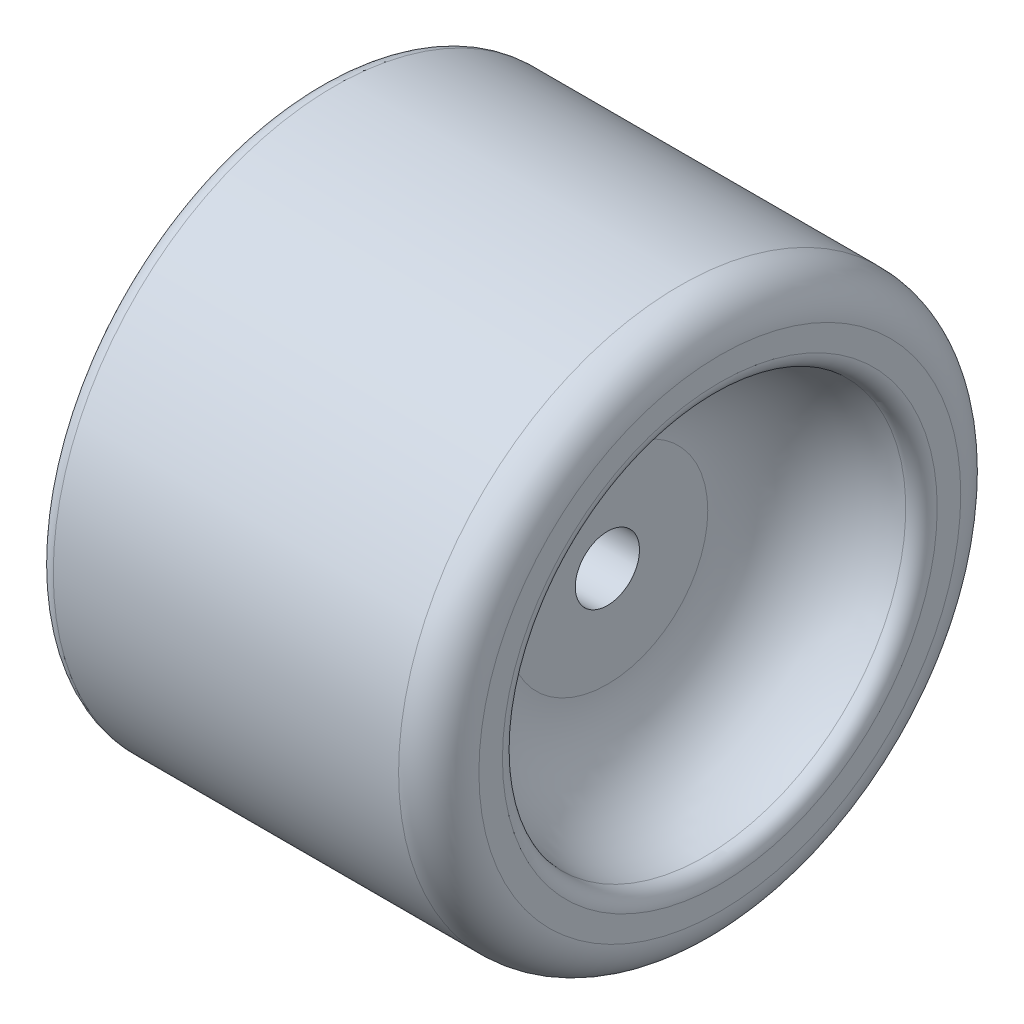
SolidWorks part; units mm, degrees
ref_plane "Front Plane" through (0, 0, 0) normal (0, 0, 1) x (1, 0, 0)
ref_plane "Top Plane" through (0, 0, 0) normal (0, 1, 0) x (1, 0, 0)
ref_plane "Right Plane" through (0, 0, 0) normal (1, 0, 0) x (0, 0, -1)
ref_plane "Plane1" through (0, 0, 0) normal (0, 0, -1) x (-1, 0, 0)
sketch "Sketch1" plane through (0, 0, 0) normal (0, 0, -1) x (-1, 0, 0)
  line L0 (0, 4) -> (22, 4)
  line L1 (22, 4) -> (22, 12.5)
  line L2 (22, 12.5) -> (24.5624, 12.5)
  line L3 (36, 29.2029) -> (36, 33)
  line L4 (34, 35) -> (-9, 35)
  line L5 (-14, 30) -> (-14, 27.0688)
  line L6 (0, 12.5) -> (0, 4)
  line L7 (-14.0021, 0) -> (36.0023, 0) construction
  arc A0 (24.5624, 12.5) -> (25.0573, 12.9284) centre (24.5624, 13) ccw
  arc A1 (25.0573, 12.9284) -> (34.9865, 27.4631) centre (44.8512, 10.0652) cw
  arc A2 (34.9865, 27.4631) -> (36, 29.2029) centre (34, 29.2029) ccw
  arc A3 (36, 33) -> (34, 35) centre (34, 33) ccw
  arc A4 (-9, 35) -> (-14, 30) centre (-9, 30) ccw
  arc A5 (-14, 27.0688) -> (-12.0796, 25.0704) centre (-12, 27.0688) ccw
  arc A6 (-12.0796, 25.0704) -> (0, 12.5) centre (-12.5804, 12.5) cw
revolve "Revolve1" add sketch "Sketch1" angle 360 about L7
